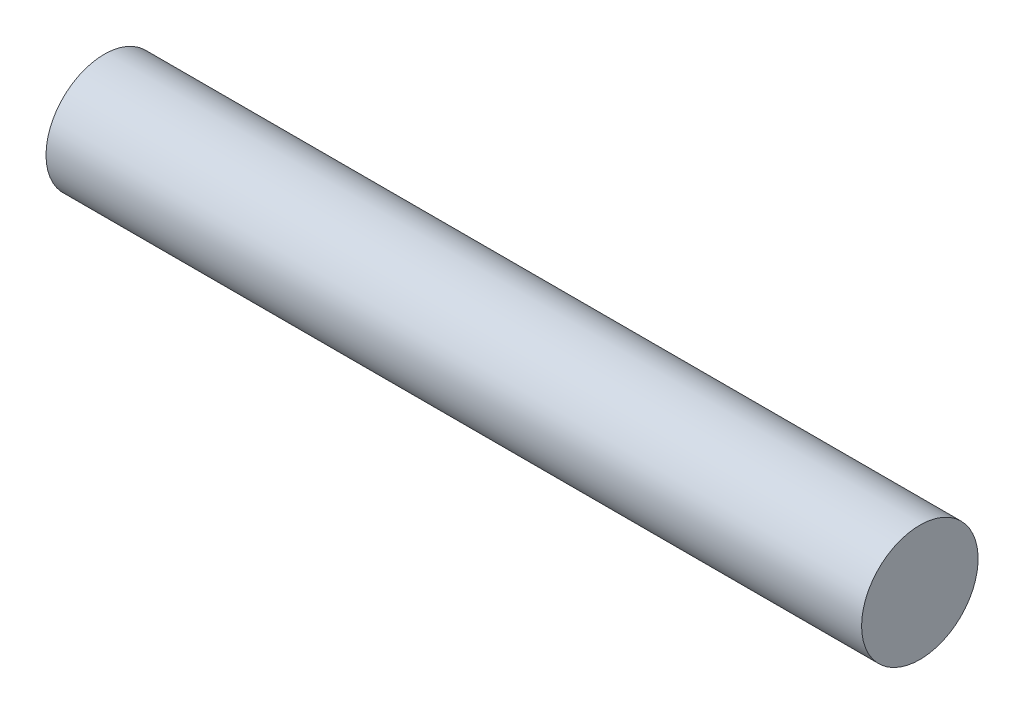
SolidWorks part; units mm, degrees
ref_plane "Front Plane" through (0, 0, 0) normal (0, 0, 1) x (1, 0, 0)
ref_plane "Top Plane" through (0, 0, 0) normal (0, 1, 0) x (1, 0, 0)
ref_plane "Right Plane" through (0, 0, 0) normal (1, 0, 0) x (0, 0, -1)
sketch "Sketch1" plane through (0, 0, 0) normal (1, 0, 0) x (0, 0, -1)
  circle A0 centre (0, 0) radius 1
  dimension "D1" = 2
extrude "Boss-Extrude1" add sketch "Sketch1" along normal mid plane 14
